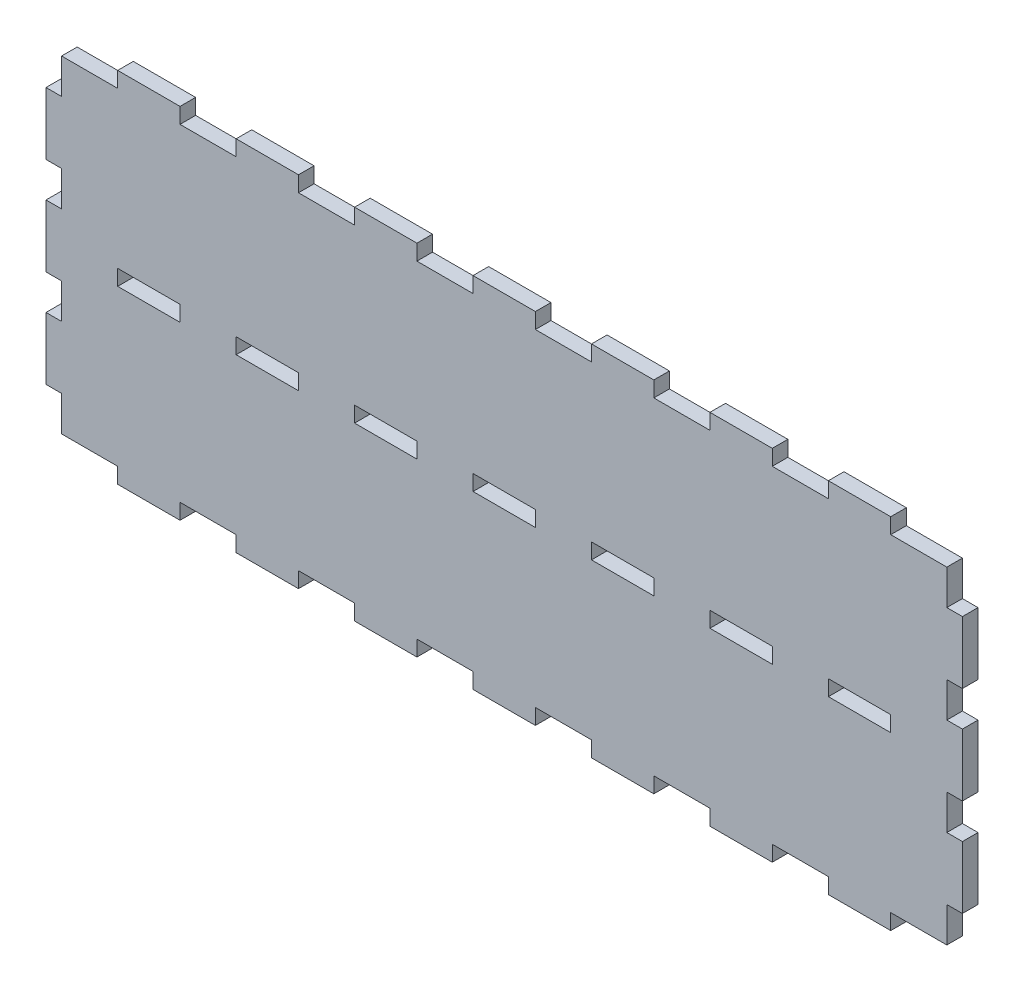
SolidWorks part; units mm, degrees
material "Beech"
ref_plane "Front" through (0, 0, 0) normal (0, 0, 1) x (1, 0, 0)
ref_plane "Top" through (0, 0, 0) normal (0, 1, 0) x (1, 0, 0)
ref_plane "Right" through (0, 0, 0) normal (1, 0, 0) x (0, 0, -1)
sketch "Sketch1" plane through (0, 0, 0) normal (0, 0, 1) x (1, 0, 0)
  line L0 (-71, 26.25) -> (71, 26.25) construction
  line L1 (-73.5, -28.75) -> (73.5, -28.75) construction
  line L2 (-73.5, -28.75) -> (-73.5, 28.75) construction
  line L3 (-73.5, 28.75) -> (73.5, 28.75) construction
  line L4 (73.5, -28.75) -> (73.5, 28.75) construction
  line L5 (-73.5, -28.75) -> (73.5, 28.75) construction
  line L6 (-73.5, 28.75) -> (73.5, -28.75) construction
  line L7 (71, -26.25) -> (71, 26.25) construction
  line L8 (-71, -26.25) -> (71, -26.25) construction
  line L9 (-71, -26.25) -> (-71, 26.25) construction
  line L10 (-71, 26.25) -> (-62, 26.25) construction
  line L11 (-62, 26.25) -> (-62, 28.75)
  line L12 (-62, 28.75) -> (-52, 28.75)
  line L13 (-52, 28.75) -> (-52, 26.25)
  line L14 (-52, 26.25) -> (-43, 26.25)
  line L15 (-43, 26.25) -> (-43, 28.75)
  line L16 (-43, 28.75) -> (-33, 28.75)
  line L17 (-33, 28.75) -> (-33, 26.25)
  line L18 (-33, 26.25) -> (-24, 26.25)
  line L19 (-24, 26.25) -> (-24, 28.75)
  line L20 (-24, 28.75) -> (-14, 28.75)
  line L21 (-14, 28.75) -> (-14, 26.25)
  line L22 (-14, 26.25) -> (-5, 26.25)
  line L23 (-5, 26.25) -> (-5, 28.75)
  line L24 (-5, 28.75) -> (5, 28.75)
  line L25 (0, 7.1682) -> (0, -8.6228) construction
  line L26 (-10.3577, 0) -> (13.2127, 0) construction
  line L27 (5, 26.25) -> (5, 28.75)
  line L28 (14, 26.25) -> (5, 26.25)
  line L29 (14, 28.75) -> (14, 26.25)
  line L30 (24, 28.75) -> (14, 28.75)
  line L31 (24, 26.25) -> (24, 28.75)
  line L32 (33, 26.25) -> (24, 26.25)
  line L33 (33, 28.75) -> (33, 26.25)
  line L34 (43, 28.75) -> (33, 28.75)
  line L35 (43, 26.25) -> (43, 28.75)
  line L36 (52, 26.25) -> (43, 26.25)
  line L37 (52, 28.75) -> (52, 26.25)
  line L38 (62, 28.75) -> (52, 28.75)
  line L39 (62, 26.25) -> (62, 28.75)
  line L40 (71, 26.25) -> (62, 26.25)
  line L41 (71, -26.25) -> (62, -26.25)
  line L42 (62, -26.25) -> (62, -28.75)
  line L43 (62, -28.75) -> (52, -28.75)
  line L44 (52, -28.75) -> (52, -26.25)
  line L45 (52, -26.25) -> (43, -26.25)
  line L46 (43, -26.25) -> (43, -28.75)
  line L47 (43, -28.75) -> (33, -28.75)
  line L48 (33, -28.75) -> (33, -26.25)
  line L49 (33, -26.25) -> (24, -26.25)
  line L50 (24, -26.25) -> (24, -28.75)
  line L51 (24, -28.75) -> (14, -28.75)
  line L52 (14, -28.75) -> (14, -26.25)
  line L53 (14, -26.25) -> (5, -26.25)
  line L54 (5, -26.25) -> (5, -28.75)
  line L55 (-5, -28.75) -> (5, -28.75)
  line L56 (-5, -26.25) -> (-5, -28.75)
  line L57 (-14, -26.25) -> (-5, -26.25)
  line L58 (-14, -28.75) -> (-14, -26.25)
  line L59 (-24, -28.75) -> (-14, -28.75)
  line L60 (-24, -26.25) -> (-24, -28.75)
  line L61 (-33, -26.25) -> (-24, -26.25)
  line L62 (-33, -28.75) -> (-33, -26.25)
  line L63 (-43, -28.75) -> (-33, -28.75)
  line L64 (-43, -26.25) -> (-43, -28.75)
  line L65 (-52, -26.25) -> (-43, -26.25)
  line L66 (-52, -28.75) -> (-52, -26.25)
  line L67 (-62, -28.75) -> (-52, -28.75)
  line L68 (-62, -26.25) -> (-62, -28.75)
  line L69 (-71, -26.25) -> (-62, -26.25) construction
  line L70 (-71, 26.25) -> (-71, 20.625)
  line L71 (-71, 20.625) -> (-73.5, 20.625)
  line L72 (-73.5, 20.625) -> (-73.5, 10.625)
  line L73 (-73.5, 10.625) -> (-71, 10.625)
  line L74 (-71, 10.625) -> (-71, 5)
  line L75 (-71, 5) -> (-73.5, 5)
  line L76 (-73.5, 5) -> (-73.5, -5)
  line L77 (-71, -5) -> (-73.5, -5)
  line L78 (-71, -10.625) -> (-71, -5)
  line L79 (-73.5, -10.625) -> (-71, -10.625)
  line L80 (-73.5, -20.625) -> (-73.5, -10.625)
  line L81 (-71, -20.625) -> (-73.5, -20.625)
  line L82 (-71, -26.25) -> (-71, -20.625)
  line L83 (71, 26.25) -> (71, 20.625)
  line L84 (71, 20.625) -> (73.5, 20.625)
  line L85 (73.5, 20.625) -> (73.5, 10.625)
  line L86 (73.5, 10.625) -> (71, 10.625)
  line L87 (71, 10.625) -> (71, 5)
  line L88 (71, 5) -> (73.5, 5)
  line L89 (73.5, 5) -> (73.5, -5)
  line L90 (71, -5) -> (73.5, -5)
  line L91 (71, -10.625) -> (71, -5)
  line L92 (73.5, -10.625) -> (71, -10.625)
  line L93 (73.5, -20.625) -> (73.5, -10.625)
  line L94 (71, -20.625) -> (73.5, -20.625)
  line L95 (71, -26.25) -> (71, -20.625)
  line L96 (-71, -26.25) -> (-62, -26.25)
  line L97 (-71, 26.25) -> (-62, 26.25)
  line L98 (-43, -1.25) -> (-43, 1.25)
  line L99 (-62, -1.25) -> (-52, -1.25)
  line L100 (-62, -1.25) -> (-62, 1.25)
  line L101 (-62, 1.25) -> (-52, 1.25)
  line L102 (-52, -1.25) -> (-52, 1.25)
  line L103 (-62, -1.25) -> (-52, 1.25) construction
  line L104 (-62, 1.25) -> (-52, -1.25) construction
  line L105 (-43, -1.25) -> (-33, -1.25)
  line L106 (-33, -1.25) -> (-33, 1.25)
  line L107 (-43, 1.25) -> (-33, 1.25)
  line L108 (-24, -1.25) -> (-24, 1.25)
  line L109 (-24, -1.25) -> (-14, -1.25)
  line L110 (-14, -1.25) -> (-14, 1.25)
  line L111 (-24, 1.25) -> (-14, 1.25)
  line L112 (-5, -1.25) -> (-5, 1.25)
  line L113 (-5, -1.25) -> (5, -1.25)
  line L114 (5, -1.25) -> (5, 1.25)
  line L115 (-5, 1.25) -> (5, 1.25)
  line L116 (14, -1.25) -> (14, 1.25)
  line L117 (14, -1.25) -> (24, -1.25)
  line L118 (24, -1.25) -> (24, 1.25)
  line L119 (14, 1.25) -> (24, 1.25)
  line L120 (33, -1.25) -> (33, 1.25)
  line L121 (33, -1.25) -> (43, -1.25)
  line L122 (43, -1.25) -> (43, 1.25)
  line L123 (33, 1.25) -> (43, 1.25)
  line L124 (52, -1.25) -> (52, 1.25)
  line L125 (52, -1.25) -> (62, -1.25)
  line L126 (62, -1.25) -> (62, 1.25)
  line L127 (52, 1.25) -> (62, 1.25)
  point P0 (0, 0)
  point P30 (0, 28.75)
  point P79 (-73.5, 0)
  point P96 (-57, 0)
  dimension "D1" = 57.5
  dimension "D2" = 147
  dimension "D4" = 9
  dimension "D5" = 10
  dimension "D6" = 5.625
  dimension "D7" = 10
  dimension "D8" = 9
  dimension "D10" = 9
  dimension "D3" = 2.5
  dimension "D9" = 7
extrude "Boss-Extrude1" add sketch "Sketch1" along normal blind 2.5
